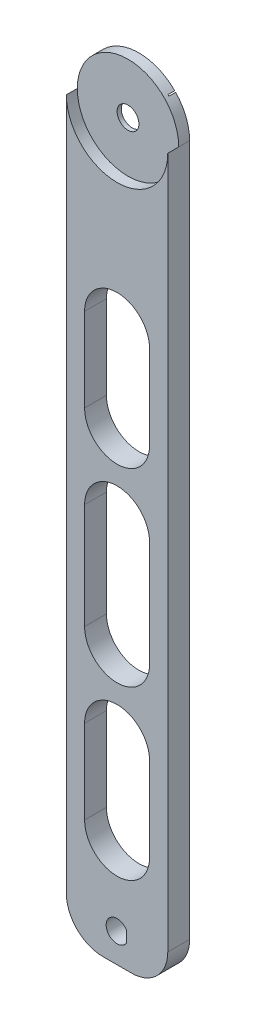
SolidWorks part; units mm, degrees
ref_plane "Plan de face" through (0, 0, 0) normal (0, 0, 1) x (1, 0, 0)
ref_plane "Plan de dessus" through (0, 0, 0) normal (0, 1, 0) x (1, 0, 0)
ref_plane "Plan de droite" through (0, 0, 0) normal (1, 0, 0) x (0, 0, -1)
sketch "Esquisse1" plane through (0, 0, 0) normal (0, 0, 1) x (1, 0, 0)
  line L1 (-12.0899, 21.2113) -> (15.7601, 21.2113)
  line L2 (-12.0899, 21.2113) -> (-12.0899, -178.7887)
  line L3 (-12.0899, -178.7887) -> (15.7601, -178.7887)
  line L4 (15.7601, 21.2113) -> (15.7601, -178.7887)
  arc A1 (15.7601, 21.2113) -> (-12.0899, 21.2113) centre (1.8351, 21.2113) ccw
  dimension "D1" = 27.85
  dimension "D2" = 200
extrude "Boss.-Extru.2" add sketch "Esquisse1" along normal blind 6 contours L4 L1 L2 L3 | L1 A1
sketch "Esquisse3" plane through (0, 0, 6) normal (0, 0, 1) x (1, 0, 0)
  line L0 (15.7601, 21.2113) -> (15.7601, -178.7887) construction
  line L1 (-12.0899, -178.7887) -> (15.7601, -178.7887) construction
  line L2 (4.4332, -169.2887) -> (4.4332, -172.2887)
  circle A0 centre (1.8351, -170.7887) radius 3
  dimension "D1" = 6
  dimension "D2" = 13.925
  dimension "D3" = 8
  dimension "D4" = 3
extrude "Enlèv. mat.-Extru.1" cut sketch "Esquisse3" against normal blind 6
sketch "Esquisse4" plane through (0, 0, 6) normal (0, 0, 1) x (1, 0, 0)
  circle A0 centre (1.8351, 21.2113) radius 13.925
extrude "Enlèv. mat.-Extru.2" cut sketch "Esquisse4" against normal blind 3
sketch "Esquisse5" plane through (0, 0, 3) normal (0, 0, 1) x (1, 0, 0)
  circle A0 centre (1.8351, 21.2113) radius 3
  dimension "D1" = 6
extrude "Enlèv. mat.-Extru.3" cut sketch "Esquisse5" against normal blind 3
sketch "Esquisse6" plane through (0, 0, 6) normal (0, 0, 1) x (1, 0, 0)
  line L0 (15.7601, 21.2113) -> (15.7601, -178.7887) construction
  line L1 (-7.0899, -27.7887) -> (10.7601, -27.7887)
  line L2 (-7.0899, -27.7887) -> (-7.0899, -50.7887)
  line L3 (-7.0899, -50.7887) -> (10.7601, -50.7887)
  line L4 (10.7601, -27.7887) -> (10.7601, -50.7887)
  line L5 (-7.0899, -73.7887) -> (10.7601, -73.7887)
  line L6 (-7.0899, -73.7887) -> (-7.0899, -102.7887)
  line L7 (-7.0899, -102.7887) -> (10.7601, -102.7887)
  line L8 (10.7601, -73.7887) -> (10.7601, -102.7887)
  line L9 (-7.0899, -125.7887) -> (10.7601, -125.7887)
  line L10 (-7.0899, -125.7887) -> (-7.0899, -148.7887)
  line L11 (-7.0899, -148.7887) -> (10.7601, -148.7887)
  line L12 (10.7601, -125.7887) -> (10.7601, -148.7887)
  line L13 (-12.0899, 21.2113) -> (-12.0899, -178.7887) construction
  line L14 (-12.0899, -178.7887) -> (15.7601, -178.7887) construction
  arc A0 (10.7601, -27.7887) -> (-7.0899, -27.7887) centre (1.8351, -27.7887) ccw
  arc A1 (-7.0899, -50.7887) -> (10.7601, -50.7887) centre (1.8351, -50.7887) ccw
  arc A2 (-7.0899, -73.7887) -> (10.7601, -73.7887) centre (1.8351, -73.7887) cw
  arc A3 (-7.0899, -102.7887) -> (10.7601, -102.7887) centre (1.8351, -102.7887) ccw
  arc A4 (10.7601, -125.7887) -> (-7.0899, -125.7887) centre (1.8351, -125.7887) ccw
  arc A5 (-7.0899, -148.7887) -> (10.7601, -148.7887) centre (1.8351, -148.7887) ccw
  dimension "D1" = 5
  dimension "D2" = 5
  dimension "D3" = 5
  dimension "D4" = 5
  dimension "D5" = 5
  dimension "D6" = 5
  dimension "D7" = 23
  dimension "D8" = 23
  dimension "D9" = 23
  dimension "D10" = 23
  dimension "D11" = 29
  dimension "D12" = 30
extrude "Enlèv. mat.-Extru.4" cut sketch "Esquisse6" against normal blind 10 contours L1 A0 | L4 L1 L2 L3 | L3 A1 | A2 L5 | L8 L5 L6 L7 | L7 A3 | L9 A4 | L12 L9 L10 L11 | L11 A5
fillet "Congé1" radius 10 1 edges at (-12.0899, -178.7887, 3)
fillet "Congé2" radius 10 1 edges at (15.7601, -178.7887, 3)
sketch "Esquisse7" plane through (0, 0, 0) normal (0, 0, -1) x (-1, 0, 0)
  circle A0 centre (-1.8351, 21.2113) radius 6.425
extrude "Enlèv. mat.-Extru.5" [suppressed] cut sketch "Esquisse7" against normal blind 1
sketch "Esquisse8" [suppressed] plane through (0, 0, 1) normal (0, 0, -1) x (-1, 0, 0)
  circle A0 centre (-1.8351, 21.2113) radius 5.56
extrude "Enlèv. mat.-Extru.6" [suppressed] cut sketch "Esquisse8" against normal blind 0.8
sketch "Esquisse9" plane through (0, 0, 0) normal (0, 0, -1) x (-1, 0, 0)
  line L1 (-11.9301, 31.0613) -> (8.2699, 31.0613)
  line L2 (-11.9301, 31.0613) -> (-11.9301, -9.2387)
  line L3 (-11.9301, -9.2387) -> (8.2699, -9.2387)
  line L4 (8.2699, 31.0613) -> (8.2699, -9.2387)
  line L6 (-15.7601, 21.2113) -> (-15.7601, -168.7887) construction
  circle A0 centre (-1.8351, 21.2113) radius 3 construction
  dimension "D1" = 20.2
  dimension "D2" = 40.3
  dimension "D3" = 9.85
  dimension "D4" = 3.83
extrude "Enlèv. mat.-Extru.7" cut sketch "Esquisse9" against normal blind 1.85
